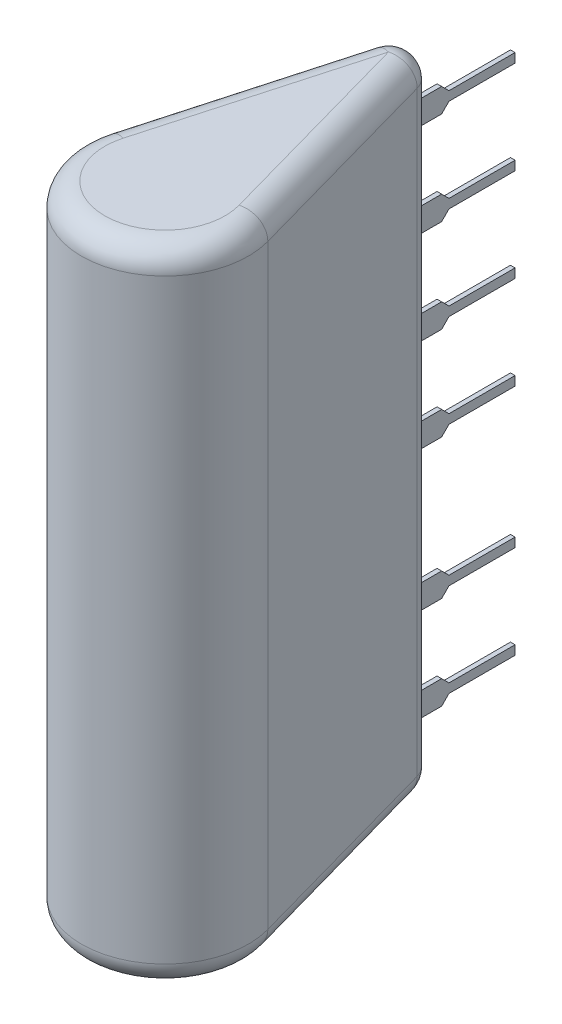
SolidWorks part; units mm, degrees
ref_plane "Front Plane" through (0, 0, 0) normal (0, 0, 1) x (1, 0, 0)
ref_plane "Top Plane" through (0, 0, 0) normal (0, 1, 0) x (1, 0, 0)
ref_plane "Right Plane" through (0, 0, 0) normal (1, 0, 0) x (0, 0, -1)
sketch "Sketch1" plane through (0, 0, 0) normal (0, 1, 0) x (1, 0, 0)
  line L0 (-4.55, -19.5) -> (-4.55, 0) construction
  line L1 (0, -19.5) -> (0, 0) construction
  line L2 (4.55, -19.5) -> (4.55, 0) construction
  line L3 (-4.55, -1.5) -> (4.55, -1.5) construction
  line L4 (-4.55, -19.5) -> (4.55, -19.5) construction
  line L5 (-4.55, 0) -> (4.55, 0) construction
  line L6 (-1.2231, -2.428) -> (-4.3819, -13.7247)
  line L7 (1.2231, -2.428) -> (4.3819, -13.7247)
  arc A0 (-4.3819, -13.7247) -> (4.3819, -13.7247) centre (0, -14.95) ccw
  arc A1 (-1.2231, -2.428) -> (1.2231, -2.428) centre (0, -2.77) cw
  dimension "D2" = 18
  dimension "D3" = 19.5
  dimension "D4" = 1.27
  dimension "D1" = 9.1
extrude "Boss-Extrude1" add sketch "Sketch1" along normal mid plane 35
fillet "Fillet1" radius 1.27 8 edges at (-2.8025, -17.5, 8.0764) (0, -17.5, 1.5) (2.8025, -17.5, 8.0764) (0, -17.5, 19.5) (-2.8025, 17.5, 8.0764) (0, 17.5, 1.5) (2.8025, 17.5, 8.0764) (0, 17.5, 19.5)
ref_plane "Plane1" through (0, 0, 2) normal (0, 0, 1) x (1, 0, 0)
sketch "Sketch2" plane through (0, 0, 2) normal (0, 0, 1) x (1, 0, 0)
  line L0 (0, 16.23) -> (0, -16.23) construction
  line L1 (0.125, 14.55) -> (-0.125, 14.55)
  line L2 (0.125, 14.55) -> (0.125, 13.25)
  line L3 (0.125, 13.25) -> (-0.125, 13.25)
  line L4 (-0.125, 14.55) -> (-0.125, 13.25)
  line L5 (1.2231, -16.23) -> (-1.2231, -16.23) construction
  line L6 (0.125, 13.9) -> (-0.125, 13.9) construction
  line L7 (3.1588, 17.5) -> (0, 17.5) construction
  point P8 (0, 14.55)
  dimension "D1" = 0.25
  dimension "D2" = 1.3
  dimension "D3" = 3.6
extrude "Boss-Extrude2" add sketch "Sketch2" against normal blind 6
sketch "Sketch3" plane through (0.125, 0, 0) normal (1, 0, 0) x (0, 0, -1)
  line L0 (4, 13.9) -> (-1.5062, 13.9) construction
  line L1 (4, 13.25) -> (4, 14.55) construction
  line L2 (-1.5062, 13.25) -> (-1.5062, 14.55) construction
  line L3 (4, 14.15) -> (0.4, 14.15)
  line L4 (0.4, 14.15) -> (0, 14.55)
  line L5 (4, 14.55) -> (-1.5062, 14.55) construction
  line L6 (0, 14.55) -> (4, 14.55)
  line L7 (4, 14.55) -> (4, 14.15)
  line L8 (4, 13.25) -> (4, 13.65)
  line L9 (4, 13.65) -> (0.4, 13.65)
  line L10 (0.4, 13.65) -> (0, 13.25)
  line L11 (0, 13.25) -> (4, 13.25)
  dimension "D1" = 4
  dimension "D2" = 45
  dimension "D3" = 0.25
extrude "Cut-Extrude1" cut sketch "Sketch3" against normal up to next
pattern_linear "LPattern1" count 4 spacing 5.08 along (0, -1, 0) of "Boss-Extrude2", "Cut-Extrude1"
sketch "Sketch4" plane through (0, 0, 2) normal (0, 0, 1) x (1, 0, 0)
  line L0 (0, 16.23) -> (0, -16.23) construction
  line L1 (0.125, -8.31) -> (-0.125, -8.31)
  line L2 (0.125, -8.31) -> (0.125, -9.61)
  line L3 (0.125, -9.61) -> (-0.125, -9.61)
  line L4 (-0.125, -8.31) -> (-0.125, -9.61)
  line L5 (-1.2231, 16.23) -> (1.2231, 16.23) construction
  line L6 (0.125, -8.96) -> (-0.125, -8.96) construction
  line L7 (0.125, -1.59) -> (0.125, -1.09) construction
  point P6 (0.125, -1.34)
  point P8 (0, -8.31)
  dimension "D1" = 0.25
  dimension "D2" = 1.3
  dimension "D3" = 7.62
extrude "Boss-Extrude3" add sketch "Sketch4" against normal blind 6
sketch "Sketch5" plane through (0.125, 0, 0) normal (1, 0, 0) x (0, 0, -1)
  line L0 (4, -8.96) -> (-1.1127, -8.96) construction
  line L3 (4, -8.71) -> (0.4, -8.71)
  line L4 (0.4, -8.71) -> (0, -8.31)
  line L6 (0, -8.31) -> (4, -8.31)
  line L7 (4, -8.31) -> (4, -8.71)
  line L8 (4, -9.61) -> (4, -9.21)
  line L9 (4, -9.21) -> (0.4, -9.21)
  line L10 (0.4, -9.21) -> (0, -9.61)
  line L11 (0, -9.61) -> (4, -9.61)
  line L12 (4, -8.31) -> (-1.5062, -8.31) construction
  line L13 (4, -9.61) -> (4, -8.31) construction
  dimension "D1" = 4
  dimension "D2" = 45
  dimension "D3" = 0.25
extrude "Cut-Extrude2" cut sketch "Sketch5" against normal up to next
pattern_linear "LPattern3" count 2 spacing 5.08 along (0, -1, 0) of "Cut-Extrude2", "Boss-Extrude3"
